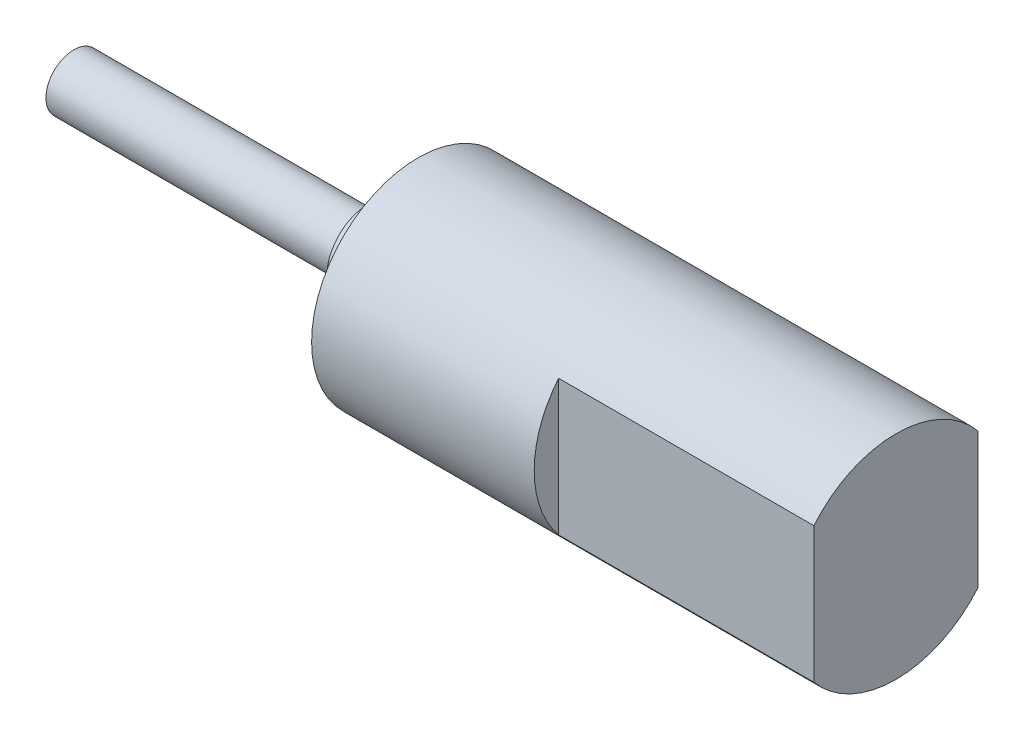
SolidWorks part; units mm, degrees
ref_plane "Front Plane" through (0, 0, 0) normal (0, 0, 1) x (1, 0, 0)
ref_plane "Top Plane" through (0, 0, 0) normal (0, 1, 0) x (1, 0, 0)
ref_plane "Right Plane" through (0, 0, 0) normal (1, 0, 0) x (0, 0, -1)
sketch "Sketch1" plane through (0, 0, 0) normal (1, 0, 0) x (0, 0, -1)
  line L0 (0, 0) -> (5.9, 0) construction
  line L1 (0, 0) -> (-5.9, 0) construction
  line L2 (-5.9, 0) -> (-5.9, 4.8774)
  line L3 (-5.9, 0) -> (-5.9, -4.8774)
  line L4 (5.9, 0) -> (5.9, 4.8774)
  line L5 (5.9, 0) -> (5.9, -4.8774)
  arc A0 (-5.9, -4.8774) -> (5.9, -4.8774) centre (0, 0) ccw
  arc A1 (5.9, 4.8774) -> (-5.9, 4.8774) centre (0, 0) ccw
  dimension "D1" = 15.31
  dimension "D2" = 5.9
  dimension "D3" = 5.9
extrude "Boss-Extrude1" add sketch "Sketch1" along normal blind 18.36
sketch "Sketch2" plane through (0, 0, 0) normal (-1, 0, 0) x (0, 0, 1)
  circle A0 centre (0, 0) radius 7.655
  dimension "D1" = 15.31
extrude "Boss-Extrude2" add sketch "Sketch2" along normal blind 16.01
sketch "Sketch3" plane through (-16.01, 0, 0) normal (-1, 0, 0) x (0, 0, 1)
  circle A0 centre (0, 0) radius 3.005
  dimension "D1" = 6.01
extrude "Boss-Extrude3" add sketch "Sketch3" along normal blind 3.56
sketch "Sketch4" plane through (-19.57, 0, 0) normal (-1, 0, 0) x (0, 0, 1)
  circle A0 centre (0, 0) radius 2
  dimension "D1" = 4
extrude "Boss-Extrude4" add sketch "Sketch4" along normal blind 21.2
sketch "Sketch5" plane through (-40.77, 0, 0) normal (-1, 0, 0) x (0, 0, 1)
  line L0 (2, 0) -> (-1.5, 0)
  line L1 (-1.5, 0) -> (-1.5, 1.3229)
  line L2 (-1.5, 0) -> (-1.5, -1.3229)
  circle A1 centre (0, 0) radius 2
  arc A2 (-1.5, -1.3229) -> (-1.5, 1.3229) centre (0, 0) ccw
  circle M5 centre (0, 0) radius 2
  dimension "D2" = 3.5
  dimension "D1" = 0
extrude "Cut-Extrude1" cut sketch "Sketch5" against normal blind 21.2 contours L2 L1 M5
